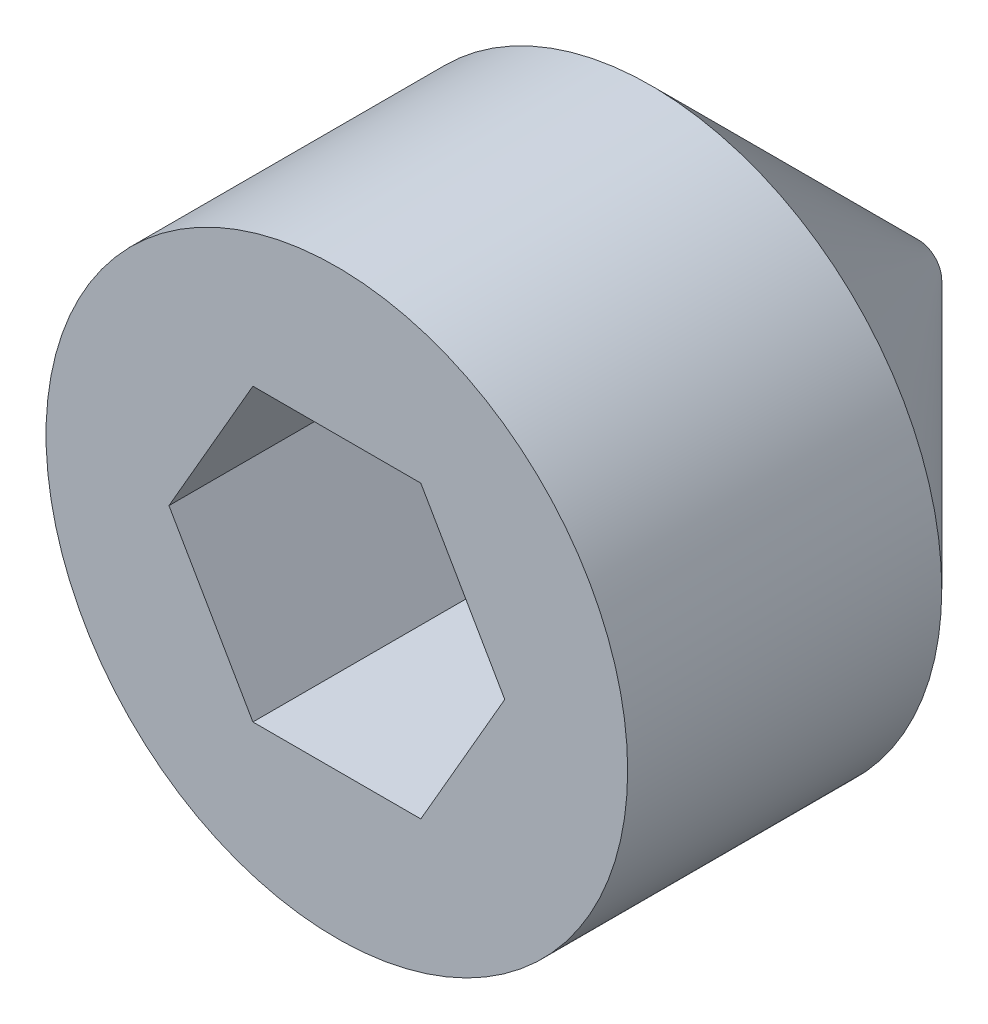
SolidWorks part; units mm, degrees
ref_plane "Front Plane" through (0, 0, 0) normal (0, 0, 1) x (1, 0, 0)
ref_plane "Top Plane" through (0, 0, 0) normal (0, 1, 0) x (1, 0, 0)
ref_plane "Right Plane" through (0, 0, 0) normal (1, 0, 0) x (0, 0, -1)
sketch "Sketch1" plane through (0, 0, 0) normal (0, 0, 1) x (1, 0, 0)
  circle A0 centre (0, 0) radius 2.5
  dimension "D1" = 5
extrude "Boss-Extrude1" add sketch "Sketch1" against normal blind 5
sketch "Sketch2" plane through (0, 0, 0) normal (0, 0, 1) x (1, 0, 0)
  line L1 (1.4434, 0) -> (0.7217, 1.25)
  line L2 (0.7217, 1.25) -> (-0.7217, 1.25)
  line L3 (-0.7217, 1.25) -> (-1.4434, 0)
  line L4 (-1.4434, 0) -> (-0.7217, -1.25)
  line L5 (-0.7217, -1.25) -> (0.7217, -1.25)
  line L6 (0.7217, -1.25) -> (1.4434, 0)
  circle A0 centre (0, 0) radius 1.25 construction
  dimension "D1" = 2.5
extrude "Cut-Extrude1" cut sketch "Sketch2" against normal blind 2
sketch3d "3DSketch1"
  line L0 (0, 0, 0) -> (0, 0, -5) construction
sketch "Sketch3" plane through (0, 0, 0) normal (1, 0, 0) x (0, 0, -1)
  line L0 (5, 2.5) -> (5, -2.5)
  line L1 (5, 2.5) -> (5, 0.2)
  line L2 (0, 0) -> (5, 0) construction
  line L3 (5, 0.2) -> (2.7, 2.5)
  line L5 (5, 2.5) -> (0, 2.5)
  line L6 (0, -0.8) -> (5, -2.5)
  line L8 (5, 2.5) -> (2.7, 2.5)
  dimension "D1" = 0.2
  dimension "D3" = 45
revolve "Chamfer" cut sketch "Sketch3" angle 360 about L0
sketch "Sketch4" plane through (0, 0, 0) normal (1, 0, 0) x (0, 0, -1)
  line L0 (5, 0.2) -> (5, -0.2)
  line L1 (5, 0.2) -> (5, 0)
  line L2 (5, 0) -> (4.9272, 0)
  line L3 (4.9272, 0) -> (5, 0.2)
  dimension "D1" = 20
revolve "Hollow" [suppressed] cut sketch "Sketch4" angle 360 about L2
sketch "Sketch5" [suppressed] plane through (0, 0, 0) normal (1, 0, 0) x (0, 0, -1)
  line L0 (0, 0) -> (5, 0) construction
  line L1 (4.25, 0) -> (5, 0) construction
  line L2 (4.25, 2.5) -> (4.25, 0) construction
  line L3 (5, 1.75) -> (5, -1.75)
  line L4 (5, 0) -> (5, -1.75) construction
  line L5 (4.25, 2.5) -> (5.25, 2.5)
  line L6 (5.25, 2.5) -> (5.25, 0)
  line L7 (5.25, 0) -> (5, 0)
  line L9 (4.25, 2.5) -> (0, 2.5)
  line L13 (0, -0.8) -> (1.8, -0.8)
  line L15 (-1, 2.5) -> (0, 2.5) construction
  arc A0 (4.25, 2.5) -> (5, 0) centre (0.4583, 0) cw
  dimension "D1" = 0.25
  dimension "D2" = 1
revolve "Domed" [suppressed] cut sketch "Sketch5" angle 360 about L7
sketch "Sketch6" [suppressed] plane through (0, 0, 0) normal (1, 0, 0) x (0, 0, -1)
  line L0 (5, 1.75) -> (5, -1.75)
  line L1 (5, 1.75) -> (5, 0) construction
  line L3 (4.25, 2.5) -> (1.75, 2.5)
  line L6 (4.25, 2.5) -> (0, 2.5)
  line L7 (5, 1.75) -> (4.25, 2.5)
  line L8 (4.25, 2.5) -> (0, 2.5) construction
  line L9 (1.75, 2.5) -> (2.5, 1.75)
  line L10 (2.5, 1.75) -> (5, 1.75)
  line L11 (0, -0.8) -> (1.8, -0.8)
  line L12 (0, 2.5) -> (0, -2.5) construction
  line L13 (0, 2.5) -> (-1, 2.5) construction
  dimension "D1" = 0.5
  dimension "D2" = 1
revolve "Dog" [suppressed] cut sketch "Sketch6" angle 360
